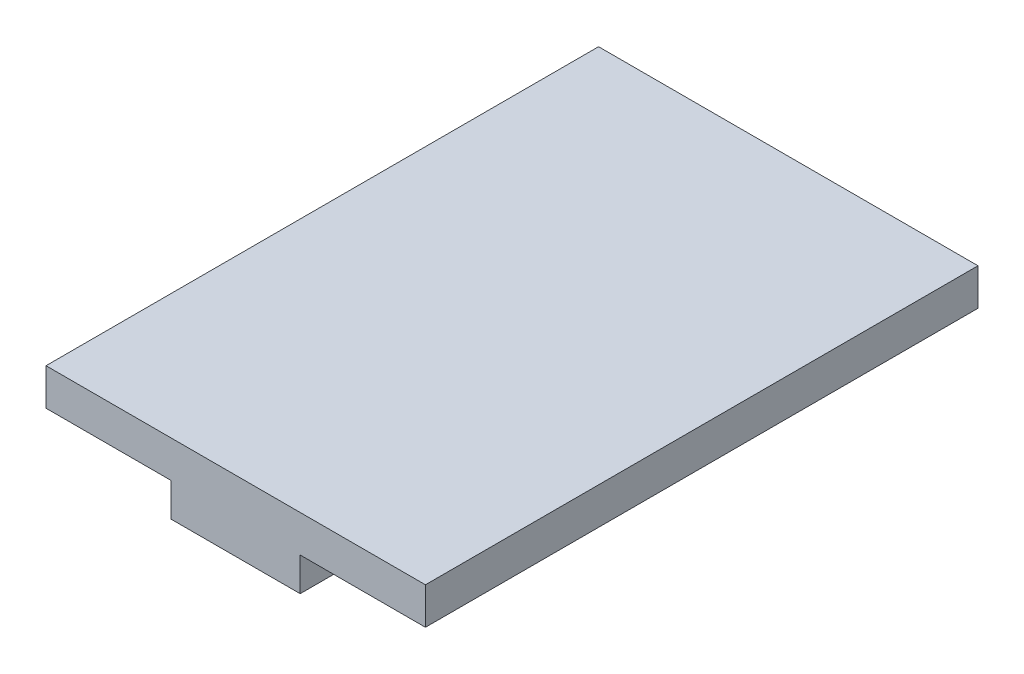
SolidWorks part; units mm, degrees
ref_plane "Front Plane" through (0, 0, 0) normal (0, 0, 1) x (1, 0, 0)
ref_plane "Top Plane" through (0, 0, 0) normal (0, 1, 0) x (1, 0, 0)
ref_plane "Right Plane" through (0, 0, 0) normal (1, 0, 0) x (0, 0, -1)
sketch "Sketch1" plane through (0, 0, 0) normal (0, 0, 1) x (1, 0, 0)
  line L1 (-10.3, 2) -> (10.3, 2)
  line L2 (-10.3, 2) -> (-10.3, 0)
  line L3 (-10.3, 0) -> (10.3, 0)
  line L4 (10.3, 2) -> (10.3, 0)
  point P4 (6.8636, 1.25)
  point P6 (0, 0)
  dimension "D1" = 2
  dimension "D2" = 20.6
extrude "Boss-Extrude1" add sketch "Sketch1" against normal blind 30
sketch "Sketch2" plane through (0, 0, 0) normal (0, 0, 1) x (1, 0, 0)
  line L0 (-10.3, 0) -> (10.3, 0) construction
  line L1 (-3.5, 0) -> (3.5, 0)
  line L2 (-3.5, 0) -> (-3.5, -1.82)
  line L3 (-3.5, -1.82) -> (3.5, -1.82)
  line L4 (3.5, 0) -> (3.5, -1.82)
  point P4 (0, 0)
  point P6 (-5.2932, 0)
  dimension "D1" = 1.82
  dimension "D2" = 7
extrude "Boss-Extrude2" add sketch "Sketch2" against normal blind 10
